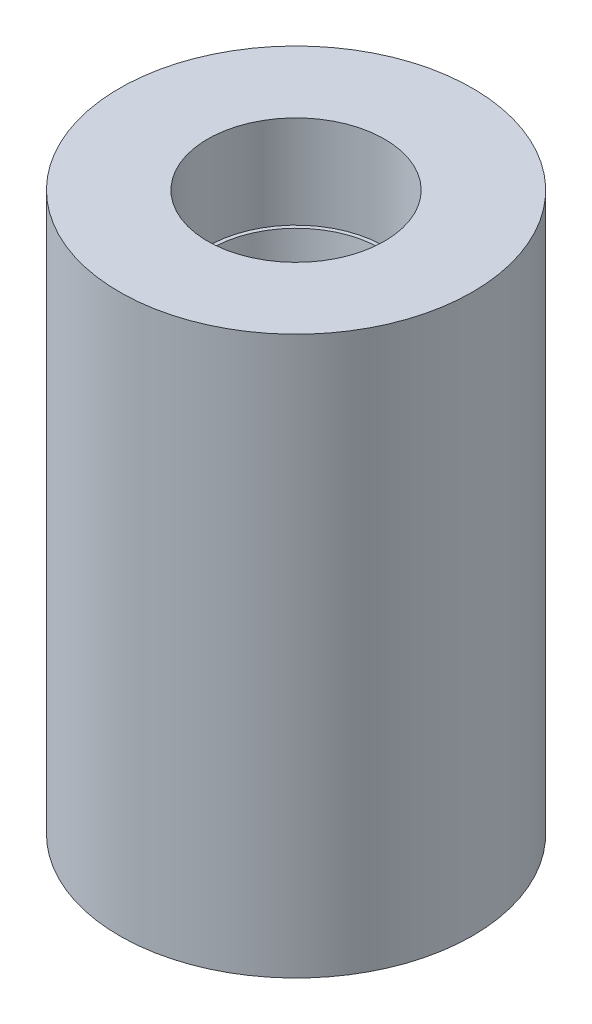
SolidWorks part; units mm, degrees
ref_plane "Front Plane" through (0, 0, 0) normal (0, 0, 1) x (1, 0, 0)
ref_plane "Top Plane" through (0, 0, 0) normal (0, 1, 0) x (1, 0, 0)
ref_plane "Right Plane" through (0, 0, 0) normal (1, 0, 0) x (0, 0, -1)
sketch "Sketch1" plane through (0, 0, 0) normal (0, 0, 1) x (1, 0, 0)
  line L0 (0, 0) -> (0, 61.074) construction
  line L1 (0, 0) -> (2.05, 0) construction
  line L2 (-0.0001, 30) -> (4.7624, 30) construction
  line L3 (4.7624, 30) -> (4.7624, 25)
  line L4 (4.7624, 25) -> (4.5592, 25)
  line L5 (2.05, 0) -> (4.5592, 25)
  line L6 (9.5, 30) -> (9.5, -0.0085)
  line L7 (9.5, -0.0085) -> (2.05, 0)
  line L8 (9.5, 30) -> (4.7624, 30)
  dimension "D1" = 2.05
  dimension "D2" = 4.7625
  dimension "D3" = 5
  dimension "D4" = 0.2032
  dimension "D5" = 30
  dimension "D6" = 9.5
revolve "Revolve1" add sketch "Sketch1" angle 360 about L0
sketch "Sketch4" plane through (0, 30, 0) normal (0, 1, 0) x (1, 0, 0)
  line L0 (0, 0) -> (9.5, 9.5) construction
  circle A0 centre (0, 0) radius 7.145 construction
  circle A1 centre (0, 7.145) radius 1.1
  circle A2 centre (7.145, 0) radius 1.1
  circle A3 centre (0, -7.145) radius 1.1
  circle A4 centre (-7.145, 0) radius 1.1
  circle A5 centre (5.0523, 5.0523) radius 0.9
  circle A6 centre (5.0523, -5.0523) radius 0.9
  circle A7 centre (-5.0523, -5.0523) radius 0.9
  circle A8 centre (-5.0523, 5.0523) radius 0.9
  point P14 (0, 0)
  point P25 (0, 0)
  dimension "D1" = 4
  dimension "D2" = 4
extrude "Cut-Extrude2" cut sketch "Sketch4" against normal blind 8 from offset 22.2
